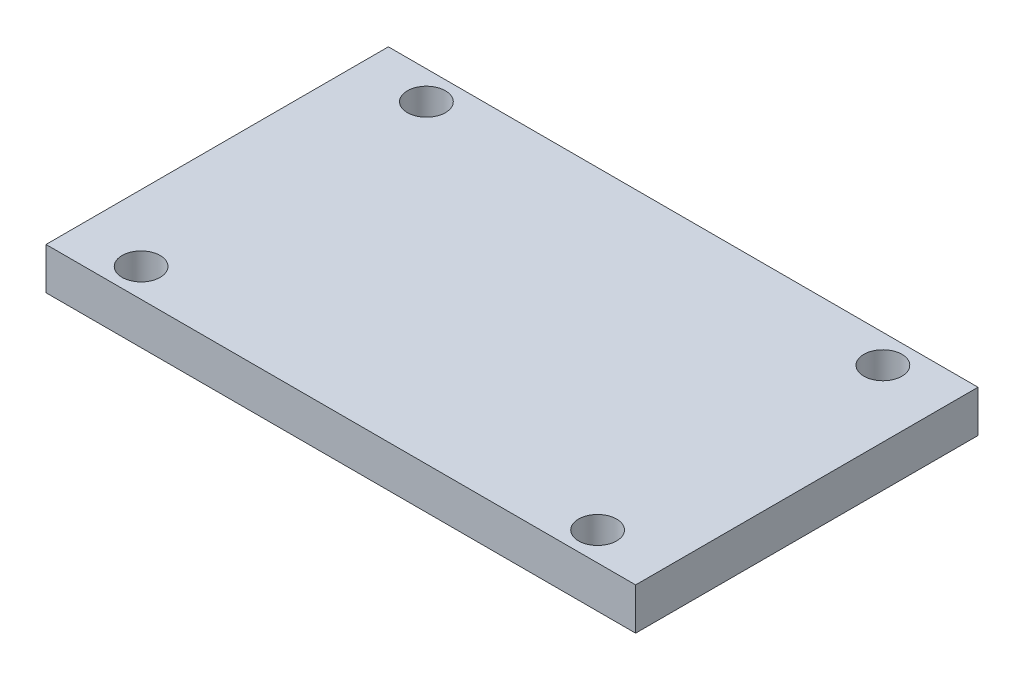
SolidWorks part; units mm, degrees
ref_plane "前视基准面" through (0, 0, 0) normal (0, 0, 1) x (1, 0, 0)
ref_plane "上视基准面" through (0, 0, 0) normal (0, 1, 0) x (1, 0, 0)
ref_plane "右视基准面" through (0, 0, 0) normal (1, 0, 0) x (0, 0, -1)
other "Configuration Table"
sketch "草图1" plane through (0, 0, 0) normal (0, 1, 0) x (1, 0, 0)
  line L1 (-77.5, 45) -> (77.5, 45)
  line L2 (-77.5, 45) -> (-77.5, -45)
  line L3 (-77.5, -45) -> (77.5, -45)
  line L4 (77.5, 45) -> (77.5, -45)
  line L5 (-77.5, 45) -> (77.5, -45) construction
  line L6 (-77.5, -45) -> (77.5, 45) construction
  point P0 (0, 0)
  dimension "D1" = 90
  dimension "D2" = 155
extrude "凸台-拉伸1" add sketch "草图1" along normal blind 11
sketch "草图2" plane through (0, 0, 0) normal (0, -1, 0) x (1, 0, 0)
  circle A0 centre (60, -37.5) radius 5
  circle A1 centre (60, 37.5) radius 5
  circle A2 centre (-60, 37.5) radius 5
  circle A3 centre (-60, -37.5) radius 5
extrude "切除-拉伸1" cut sketch "草图2" against normal through all
